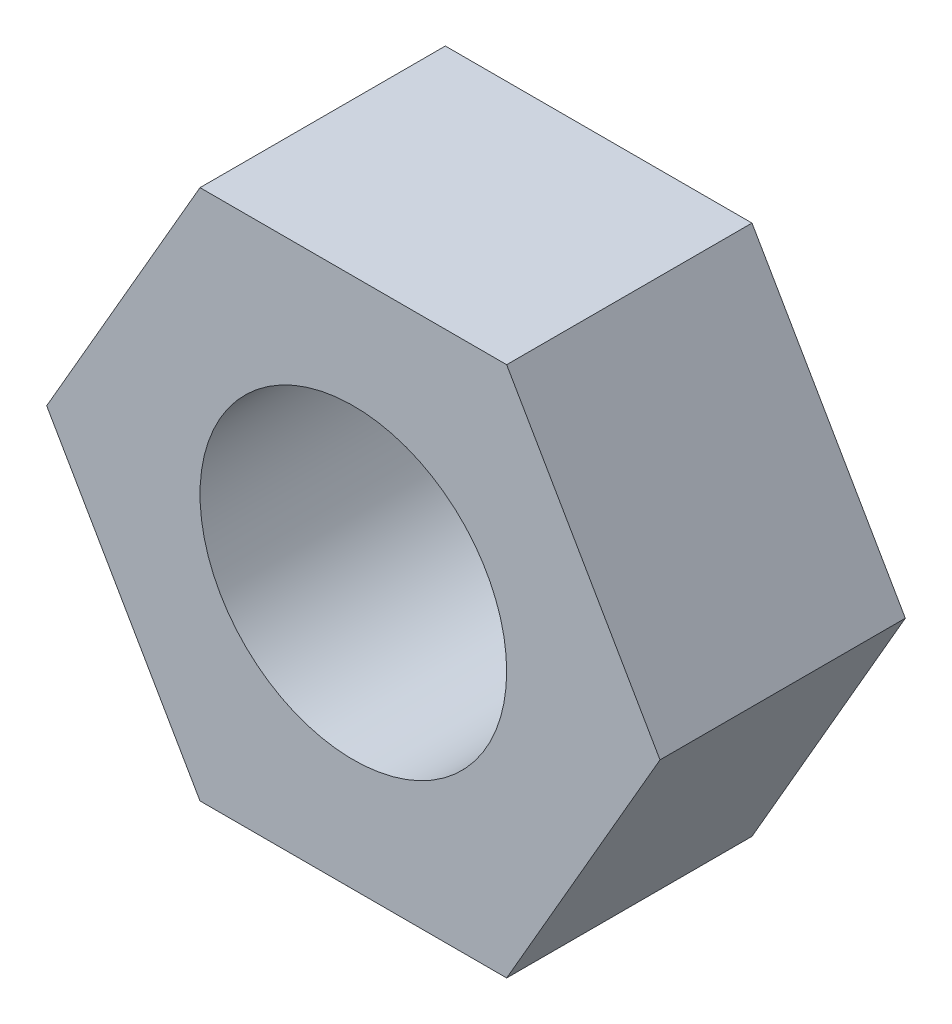
SolidWorks part; units mm, degrees
ref_plane "Front Plane" through (0, 0, 0) normal (0, 0, 1) x (1, 0, 0)
ref_plane "Top Plane" through (0, 0, 0) normal (0, 1, 0) x (1, 0, 0)
ref_plane "Right Plane" through (0, 0, 0) normal (1, 0, 0) x (0, 0, -1)
sketch "Sketch1" plane through (0, 0, 0) normal (0, 0, 1) x (1, 0, 0)
  line L1 (5, 0) -> (2.5, 4.3301)
  line L2 (2.5, 4.3301) -> (-2.5, 4.3301)
  line L3 (-2.5, 4.3301) -> (-5, 0)
  line L4 (-5, 0) -> (-2.5, -4.3301)
  line L5 (-2.5, -4.3301) -> (2.5, -4.3301)
  line L6 (2.5, -4.3301) -> (5, 0)
  circle A0 centre (0, 0) radius 4.3301 construction
  dimension "D1" = 10
extrude "Boss-Extrude1" add sketch "Sketch1" along normal blind 4
sketch "Sketch2" plane through (0, 0, 4) normal (0, 0, 1) x (1, 0, 0)
  circle A0 centre (0, 0) radius 2.5
  dimension "D1" = 5
extrude "Cut-Extrude1" cut sketch "Sketch2" against normal through all contours A0
